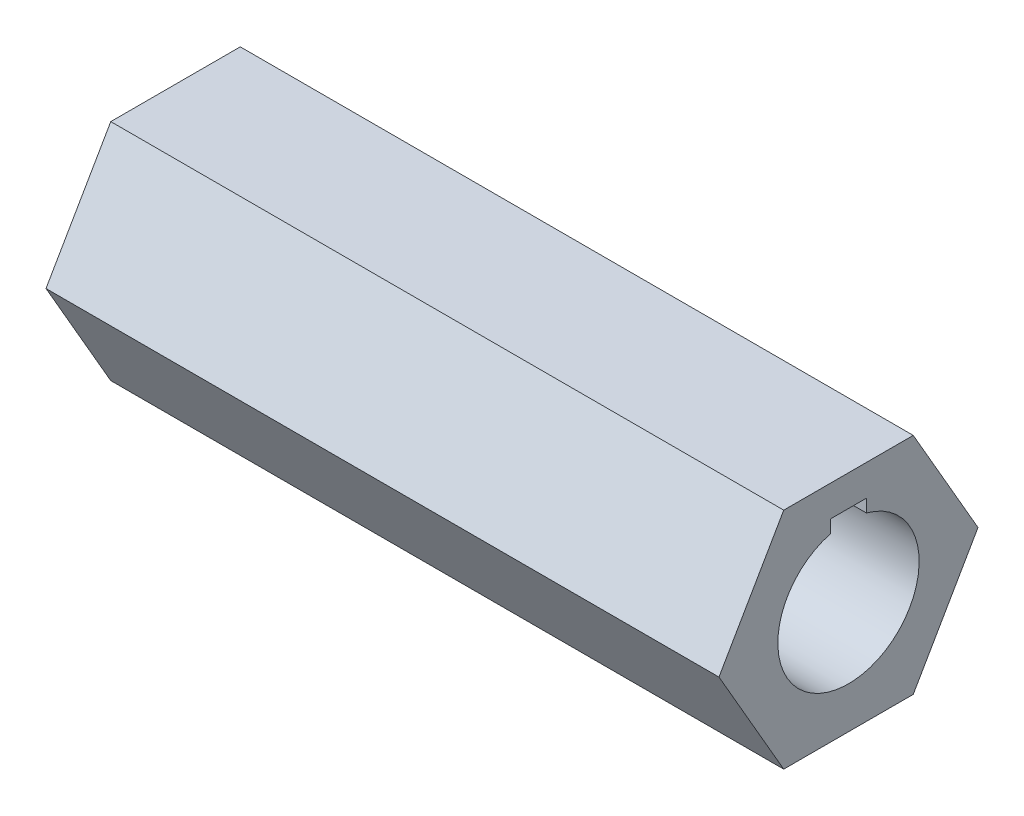
SolidWorks part; units mm, degrees
ref_plane "Front" through (0, 0, 0) normal (0, 0, 1) x (1, 0, 0)
ref_plane "Top" through (0, 0, 0) normal (0, 1, 0) x (1, 0, 0)
ref_plane "Right" through (0, 0, 0) normal (1, 0, 0) x (0, 0, -1)
sketch "Sketch1" plane through (0, 0, 0) normal (1, 0, 0) x (0, 0, -1)
  line L1 (7.3323, 0) -> (3.6662, 6.35)
  line L2 (3.6662, 6.35) -> (-3.6662, 6.35)
  line L3 (-3.6662, 6.35) -> (-7.3323, 0)
  line L4 (-7.3323, 0) -> (-3.6662, -6.35)
  line L5 (-3.6662, -6.35) -> (3.6662, -6.35)
  line L6 (3.6662, -6.35) -> (7.3323, 0)
  circle A0 centre (0, 0) radius 6.35 construction
  dimension "D1" = 12.7
extrude "Boss-Extrude1" add sketch "Sketch1" along normal blind 38.1
sketch "Sketch2" plane through (38.1, 0, 0) normal (1, 0, 0) x (0, 0, -1)
  circle A1 centre (0, 0) radius 4
  dimension "D2" = 8
extrude "Cut-Extrude1" cut sketch "Sketch2" against normal through all
sketch "Sketch3" plane through (0, 0, 0) normal (-1, 0, 0) x (0, 0, 1)
  line L1 (-1.016, 3.4031) -> (1.016, 3.4031)
  line L2 (-1.016, 3.4031) -> (-1.016, 4.5969)
  line L3 (-1.016, 4.5969) -> (1.016, 4.5969)
  line L4 (1.016, 3.4031) -> (1.016, 4.5969)
  line L5 (-1.016, 3.4031) -> (1.016, 4.5969) construction
  line L6 (-1.016, 4.5969) -> (1.016, 3.4031) construction
  circle A1 centre (0, 0) radius 4 construction
  point P0 (0, 4)
  point P5 (0, 3.9678)
  point P6 (0, 0)
  point P7 (0, 0)
  point P9 (0, 4.381)
  dimension "D1" = 2.032
  dimension "D2" = 1.1938
extrude "Cut-Extrude2" cut sketch "Sketch3" against normal through all
